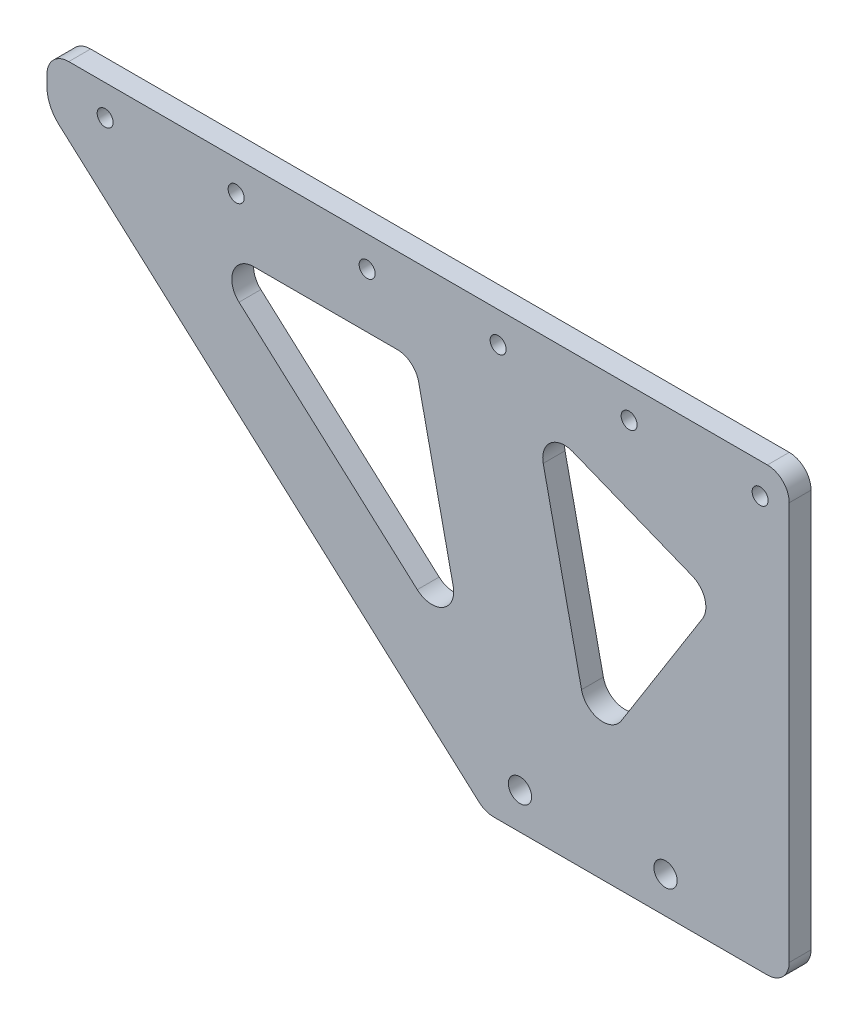
SolidWorks part; units mm, degrees
material "Thornel Mat VMA"
ref_plane "Front" through (0, 0, 0) normal (0, 0, 1) x (1, 0, 0)
ref_plane "Top" through (0, 0, 0) normal (0, 1, 0) x (1, 0, 0)
ref_plane "Right" through (0, 0, 0) normal (1, 0, 0) x (0, 0, -1)
sketch "草图1" plane through (0, 0, 0) normal (0, 0, 1) x (1, 0, 0)
  line L0 (0, 0) -> (0, -57)
  line L1 (0, -57) -> (-42, -57)
  line L2 (-42, -57) -> (-100, -5)
  line L3 (-100, -5) -> (-100, 0)
  line L4 (-100, 0) -> (0, 0)
  dimension "D1" = 57
  dimension "D2" = 100
  dimension "D3" = 42
  dimension "D4" = 5
extrude "凸台-拉伸1" add sketch "草图1" along normal blind 3
sketch "草图2" plane through (0, 0, 3) normal (0, 0, 1) x (1, 0, 0)
  line L0 (0, -57) -> (0, 0) construction
  line L1 (-20, 0) -> (-20, -50000) construction
  line L2 (0, 0) -> (-100, 0) construction
  line L3 (-42, -57) -> (0, -57) construction
  line L4 (-2, -2.5) -> (-99.7924, -2.5) construction
  line L5 (-2, -2.5) -> (-2, -54) construction
  line L6 (-2, -54) -> (-42.3501, -54) construction
  line L7 (-42.3501, -54) -> (-99.7924, -2.5) construction
  line L8 (-100, -5) -> (-42, -57) construction
  circle A0 centre (-38, -45) radius 1.1
  circle A1 centre (-38, -14.5) radius 1.1
  circle A2 centre (-38, -2.5) radius 1.1
  circle A3 centre (-56, -2.5) radius 1.1
  circle A4 centre (-74, -2.5) radius 1.1
  circle A5 centre (-92, -2.5) radius 1.1
  circle A6 centre (-55.0078, -42.6517) radius 1.025
  circle A8 centre (-81.2232, -24.3009) radius 1.025
  circle A112 centre (-20, -2.5) radius 1.1
  circle A115 centre (-2, -2.5) radius 1.1
  circle A118 centre (-2, -14.5) radius 1.1
  circle A121 centre (-2, -45) radius 1.1
  circle A124 centre (-15, -54) radius 1.6
  circle A127 centre (-35, -54) radius 1.6
  circle A128 centre (-68.1155, -33.4763) radius 1.025 [skipped]
  dimension "D3" = 3.2
  dimension "D4" = 3.2
  dimension "D10" = 2.2
  dimension "D11" = 2.2
  dimension "D12" = 2.2
  dimension "D13" = 2.2
  dimension "D18" = 2.05
  dimension "D1" = 20
  dimension "D2" = 15
  dimension "D5" = 3
  dimension "D6" = 12
  dimension "D7" = 12
  dimension "D8" = 2.5
  dimension "D9" = 2
  dimension "D14" = 30.5
  dimension "D15" = 20
  dimension "D16" = 18
  dimension "D17" = 2
  dimension "D19" = 3
  dimension "D20" = 17
extrude "切除-拉伸2" cut sketch "草图2" against normal through all
fillet "圆角1" radius 5 1 edges at (-100, -5, 1.5)
sketch "草图3" plane through (0, 0, 3) normal (0, 0, 1) x (1, 0, 0)
  line L5 (-100, 0) -> (-100, -2.7675)
  line L6 (-98.3377, -6.4903) -> (-42, -57)
  line L7 (-42, -57) -> (0, -57)
  line L8 (0, -57) -> (0, 0)
  line L9 (0, 0) -> (-100, 0)
  line L10 (-100, 0) -> (-100, -2.7675)
  line L11 (-98.3377, -6.4903) -> (-42, -57)
  line L12 (-42, -57) -> (0, -57)
  line L13 (0, -57) -> (0, 0)
  line L14 (0, 0) -> (-100, 0)
  circle A0 centre (-92, -2.5) radius 1.1 construction
  arc A1 (-100, -2.7675) -> (-98.3377, -6.4903) centre (-95, -2.7675) ccw
  arc A2 (-100, -2.7675) -> (-98.3377, -6.4903) centre (-95, -2.7675) ccw
  circle A3 centre (-15, -54) radius 1.6
  circle A4 centre (-15, -54) radius 1.6
  circle A5 centre (-35, -54) radius 1.6
  circle A6 centre (-35, -54) radius 1.6
  circle A7 centre (-2, -2.5) radius 1.1
  circle A8 centre (-2, -2.5) radius 1.1
  circle A9 centre (-20, -2.5) radius 1.1
  circle A10 centre (-20, -2.5) radius 1.1
  circle A11 centre (-38, -2.5) radius 1.1
  circle A12 centre (-38, -2.5) radius 1.1
  circle A13 centre (-56, -2.5) radius 1.1
  circle A14 centre (-56, -2.5) radius 1.1
  circle A15 centre (-74, -2.5) radius 1.1
  circle A16 centre (-74, -2.5) radius 1.1
  circle A17 centre (-92, -2.5) radius 1.1
  dimension "D1" = 0
  dimension "D2" = 0
  dimension "D3" = 0
  dimension "D4" = 0
  dimension "D5" = 0
  dimension "D6" = 0
  dimension "D7" = 0
  dimension "D8" = 0
extrude "凸台-拉伸2" add sketch "草图3" against normal up to surface (3 mm away) up to face at (-13.4, -54, 0)
sketch "草图4" plane through (0, 0, 3) normal (0, 0, 1) x (1, 0, 0)
  line L0 (-79.4428, -10) -> (-42.2143, -43.3773)
  line L1 (-98.3377, -6.4903) -> (-42, -57) construction
  line L2 (-79.4428, -10) -> (-49.4428, -10)
  line L3 (-49.4428, -10) -> (-42.2143, -43.3773)
  line L4 (0, 0) -> (-100, 0) construction
  line L5 (-33, -8) -> (-8, -18)
  line L6 (-8, -18) -> (-24.987, -45)
  line L7 (-24.987, -45) -> (-33, -8)
  line L8 (0, -57) -> (0, 0) construction
  line L9 (-42, -57) -> (0, -57) construction
  point P12 (-49.66, -36.7018)
  point P13 (-29.4659, -56.6407)
  point P14 (-29.4659, -56.6407)
  point P15 (-29.4659, -56.6407)
  point P16 (-29.4659, -56.6407)
  point P17 (-10, -18.2084)
  point P18 (-32.8343, -41.0873)
  point P19 (-32.5452, -42.4223)
  point P20 (-10, -16.8683)
  point P21 (-33, -8)
  point P22 (-24.8956, -45.4219)
  dimension "D1" = 50
  dimension "D2" = 10
  dimension "D3" = 30
  dimension "D4" = 10
  dimension "D5" = 18
  dimension "D6" = 25
  dimension "D7" = 12
  dimension "D8" = 8
  dimension "D9" = 8
extrude "切除-拉伸3" cut sketch "草图4" against normal blind 10
fillet "圆角2" radius 3 6 edges at (-8, -18, 1.5) (-24.987, -45, 1.5) (-49.4428, -10, 1.5) (-42.2143, -43.3773, 1.5) (-79.4428, -10, 1.5) (-33, -8, 1.5)
sketch "草图5" plane through (0, 0, 3) normal (0, 0, 1) x (1, 0, 0)
  line L0 (-47.0883, -52.4381) -> (-39.7692, -59)
  line L1 (-98.3377, -6.4903) -> (-42, -57) construction
  line L2 (-39.7692, -59) -> (0, -59)
  line L3 (0, -59) -> (0, -57)
  line L4 (0, -57) -> (-42, -57)
  line M27 (-42, -57) -> (0, -57)
  dimension "D1" = 2
extrude "凸台-拉伸3" add sketch "草图5" against normal up to surface (3 mm away) contours L2 L3 L0 M27 up to face at (-56.6041, -19.9516, 0)
fillet "圆角3" [suppressed] radius 3
sketch "草图6" plane through (0, 0, 0) normal (1, 0, 0) x (0, 0, -1)
  line L4 (0, -59) -> (0, 0)
  line L5 (0, 0) -> (-3, 0)
  line L6 (-3, 0) -> (-3, -59)
  line L7 (-3, -59) -> (0, -59)
  line L8 (0, -59) -> (0, 0)
  line L9 (0, 0) -> (-3, 0)
  line L10 (-3, 0) -> (-3, -59)
  line L11 (-3, -59) -> (0, -59)
  dimension "D1" = 0
extrude "凸台-拉伸4" add sketch "草图6" along normal blind 2
sketch "草图7" plane through (0, 0, 0) normal (0, 1, 0) x (1, 0, 0)
  line L4 (2, 0) -> (-100, 0)
  line L5 (-100, 0) -> (-100, -3)
  line L6 (-100, -3) -> (2, -3)
  line L7 (2, -3) -> (2, 0)
  line L8 (2, 0) -> (-100, 0)
  line L9 (-100, 0) -> (-100, -3)
  line L10 (-100, -3) -> (2, -3)
  line L11 (2, -3) -> (2, 0)
  dimension "D1" = 0
extrude "凸台-拉伸5" add sketch "草图7" along normal blind 1.7
fillet "圆角4" radius 3 4 edges at (-100, 1.7, 1.5) (2, -59, 1.5) (-39.7692, -59, 1.5) (2, 1.7, 1.5)
